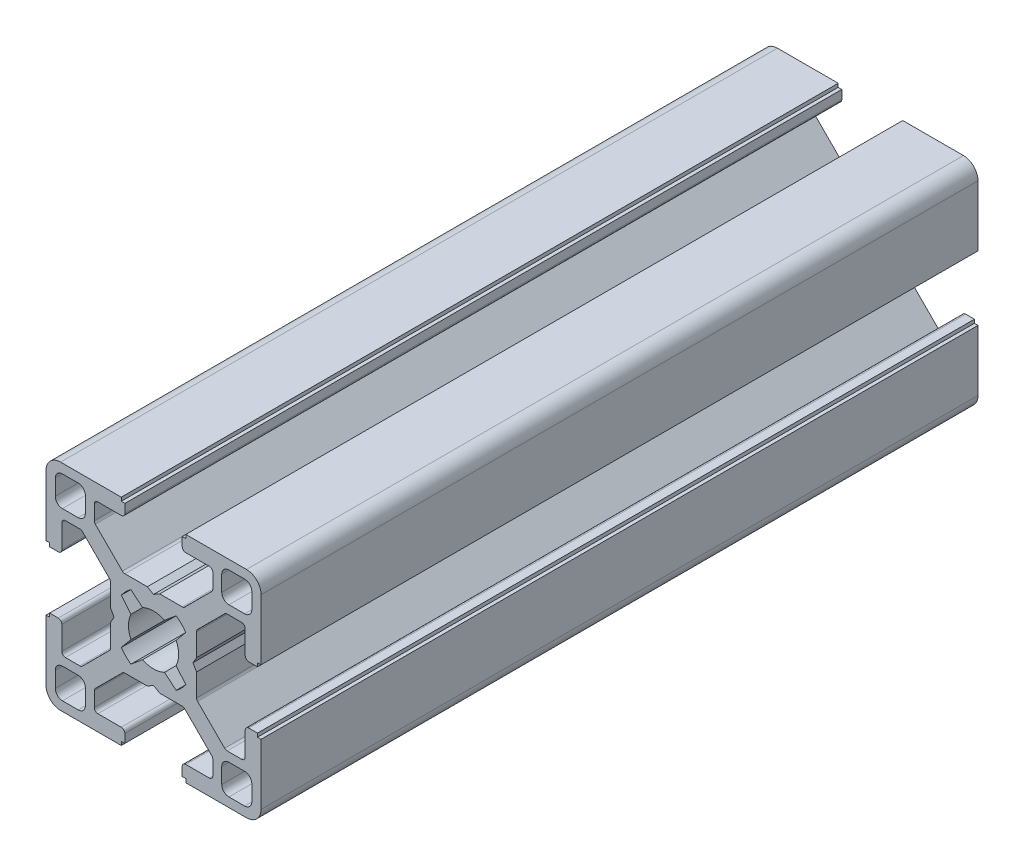
SolidWorks part; units mm, degrees
ref_plane "Front Plane" through (0, 0, 0) normal (0, 0, 1) x (1, 0, 0)
ref_plane "Top Plane" through (0, 0, 0) normal (0, 1, 0) x (1, 0, 0)
ref_plane "Right Plane" through (0, 0, 0) normal (1, 0, 0) x (0, 0, -1)
sketch "Sketch1" plane through (0, 0, 0) normal (0, 0, 1) x (1, 0, 0)
  line L0 (-15, 0) -> (15, 0) construction
  line L1 (0, -15) -> (0, 15) construction
  line L2 (-4.5, 15) -> (4.5, 15) construction
  line L3 (-4, -15) -> (4, -15) construction
  line L4 (-4.5, 15) -> (-4.5, 14.5)
  line L5 (-4.5, 14.5) -> (-4, 14.5)
  line L6 (-4, 14.5) -> (-4, 13.29)
  line L7 (-4.5, 12.79) -> (-7.7675, 12.79)
  line L8 (-8.2675, 12.29) -> (-8.2675, 10.2707)
  line L9 (-8.1211, 9.9171) -> (-4.3504, 6.1464)
  line L10 (-3.9968, 6) -> (0, 6)
  line L11 (0, 0) -> (-15, 15) construction
  line L12 (-4.5, 15) -> (-12.968, 15)
  line L14 (-12.705, 9.5135) -> (-10.5135, 9.5135)
  line L15 (-13.705, 10.5135) -> (-13.705, 12.705)
  line L16 (-12.705, 13.705) -> (-10.5135, 13.705)
  line L17 (-9.5135, 10.5135) -> (-9.5135, 12.705)
  line L18 (-13.705, 9.5135) -> (-9.5135, 13.705) construction
  line L19 (-13.705, 13.705) -> (-9.5135, 9.5135) construction
  line L20 (-3.1568, 4.5038) -> (-1.5303, 3.1477) construction
  line L21 (-4.5038, 3.1568) -> (-3.1477, 1.5303) construction
  line L22 (-6, 3.9968) -> (-6, 0)
  line L23 (-9.9171, 8.1211) -> (-6.1464, 4.3504)
  line L24 (-15, 4.5) -> (-15, 12.968)
  line L25 (-12.29, 8.2675) -> (-10.2707, 8.2675)
  line L26 (-12.79, 4.5) -> (-12.79, 7.7675)
  line L27 (-14.5, 4) -> (-13.29, 4)
  line L28 (-14.5, 4.5) -> (-14.5, 4)
  line L29 (-15, 4.5) -> (-14.5, 4.5)
  circle A0 centre (0, 0) radius 3.5
  arc A1 (-12.968, 15) -> (-15, 12.968) centre (-12.968, 12.968) ccw
  circle A2 centre (0, 0) radius 5.5 construction
  arc A3 (-10.5135, 9.5135) -> (-9.5135, 10.5135) centre (-10.5135, 10.5135) ccw
  arc A4 (-13.705, 12.705) -> (-12.705, 13.705) centre (-12.705, 12.705) cw
  arc A5 (-10.5135, 13.705) -> (-9.5135, 12.705) centre (-10.5135, 12.705) cw
  arc A6 (-12.705, 9.5135) -> (-13.705, 10.5135) centre (-12.705, 10.5135) cw
  arc A7 (-12.79, 4.5) -> (-13.29, 4) centre (-13.29, 4.5) cw
  arc A8 (-12.29, 8.2675) -> (-12.79, 7.7675) centre (-12.29, 7.7675) ccw
  arc A9 (-9.9171, 8.1211) -> (-10.2707, 8.2675) centre (-10.2707, 7.7675) ccw
  arc A10 (-6, 3.9968) -> (-6.1464, 4.3504) centre (-6.5, 3.9968) ccw
  arc A11 (-4.3504, 6.1464) -> (-3.9968, 6) centre (-3.9968, 6.5) ccw
  arc A12 (-4, 13.29) -> (-4.5, 12.79) centre (-4.5, 13.29) cw
  arc A13 (-7.7675, 12.79) -> (-8.2675, 12.29) centre (-7.7675, 12.29) ccw
  arc A14 (-8.2675, 10.2707) -> (-8.1211, 9.9171) centre (-7.7675, 10.2707) ccw
  point P4 (0, 0)
  point P8 (0, 0)
  point P13 (0, 15)
  point P15 (0, -15)
  point P16 (0, 6)
  point P23 (-11.6092, 11.6093)
  point P26 (0, 6)
  point P62 (-12.79, 4)
  point P65 (-12.79, 8.2675)
  point P68 (-10.0636, 8.2675)
  point P71 (-6, 4.2039)
  point P74 (-4.2039, 6)
  point P77 (-4, 12.79)
  point P80 (-8.2675, 12.79)
  point P83 (-8.2675, 10.0636)
  dimension "Center Hole Diameter" = 7
  dimension "D11" = 2.032
  dimension "D9" = 11
  dimension "D13" = 1
  dimension "D14" = 0.5
  dimension "Rail Height" = 30
  dimension "Rail Width" = 30
  dimension "T-Slot Width" = 8
  dimension "T-Slot Depth" = 9
  dimension "D1" = 9
  dimension "D2" = 45
  dimension "D3" = 8
  dimension "D4" = 2.21
  dimension "D5" = 16.535
  dimension "D7" = 2.54
  dimension "D6" = 1.295
  dimension "D8" = 1.246
  dimension "D10" = 10.36
  dimension "D12" = 1.905
sketch "Sketch2" plane through (0, 0, 0) normal (1, 0, 0) x (0, 0, -1)
  line L0 (-76.2, 0) -> (76.2, 0) construction
  line L2 (0, -15) -> (0, 15) construction
  line L3 (0, -15) -> (0, 15) construction
  line L4 (-76.2, -15) -> (-76.2, 15) construction
  line L5 (76.2, -15) -> (76.2, 15) construction
  point P0 (-38.7, 0)
  point P3 (0, 0)
  point P4 (38.7, 0)
  point P12 (-76.2, 0)
  point P14 (76.2, 0)
  dimension "Length" = 152.4
  dimension "D1" = 37.5
sketch "Sketch3" plane through (0, 0, 0) normal (0, 0, 1) x (1, 0, 0)
  line L0 (-4.5038, 3.1568) -> (-3.1477, 1.5303)
  line L1 (0, 3.5) -> (0, 5.5)
  line L2 (-5.5, 0) -> (-3.5, 0)
  line L7 (-6, 3.9968) -> (-6, 0) construction
  line L31 (-9.9171, 8.1211) -> (-6.1464, 4.3504) construction
  line L117 (-12.29, 8.2675) -> (-10.2707, 8.2675) construction
  line L118 (-12.79, 4.5) -> (-12.79, 7.7675) construction
  line L157 (-12.705, 9.5135) -> (-10.5135, 9.5135)
  line L158 (-9.5135, 10.5135) -> (-9.5135, 12.705)
  line L163 (-10.5135, 13.705) -> (-12.705, 13.705)
  line L164 (-13.705, 12.705) -> (-13.705, 10.5135)
  line L165 (-12.705, 9.5135) -> (-10.5135, 9.5135)
  line L166 (-9.5135, 10.5135) -> (-9.5135, 12.705)
  line L167 (-10.5135, 13.705) -> (-12.705, 13.705)
  line L168 (-13.705, 12.705) -> (-13.705, 10.5135)
  line L169 (-14.5, 4) -> (-13.29, 4) construction
  line L170 (-14.5, 4.5) -> (-14.5, 4) construction
  line L171 (-15, 4.5) -> (-14.5, 4.5) construction
  line L172 (-15, 4.5) -> (-15, 12.968) construction
  line L173 (-4.5, 15) -> (-12.968, 15) construction
  line L174 (-4.5, 15) -> (-4.5, 14.5) construction
  line L175 (-4.5, 14.5) -> (-4, 14.5) construction
  line L176 (-4, 14.5) -> (-4, 13.29) construction
  line L177 (-4.5, 12.79) -> (-7.7675, 12.79) construction
  line L178 (-8.2675, 12.29) -> (-8.2675, 10.2707) construction
  line L179 (-8.1211, 9.9171) -> (-4.3504, 6.1464) construction
  line L180 (-3.9968, 6) -> (0, 6) construction
  line L181 (-6, 3.9968) -> (-6, 0.866)
  line L182 (-9.9171, 8.1211) -> (-6.1464, 4.3504)
  line L183 (-12.29, 8.2675) -> (-10.2707, 8.2675)
  line L184 (-12.79, 4.5) -> (-12.79, 7.7675)
  line L185 (-14.5, 4) -> (-13.29, 4)
  line L186 (-14.5, 4.5) -> (-14.5, 4)
  line L187 (-15, 4.5) -> (-14.5, 4.5)
  line L188 (-15, 4.5) -> (-15, 12.968)
  line L189 (-4.5, 15) -> (-12.968, 15)
  line L190 (-4.5, 15) -> (-4.5, 14.5)
  line L191 (-4.5, 14.5) -> (-4, 14.5)
  line L192 (-4, 14.5) -> (-4, 13.29)
  line L193 (-4.5, 12.79) -> (-7.7675, 12.79)
  line L194 (-8.2675, 12.29) -> (-8.2675, 10.2707)
  line L195 (-8.1211, 9.9171) -> (-4.3504, 6.1464)
  line L196 (-3.9968, 6) -> (-0.866, 6)
  line L197 (-0.866, 6) -> (0, 5.5)
  line L198 (0, -15) -> (0, 15) construction
  line L199 (0, 0) -> (-15, 15) construction
  line L200 (0, 0) -> (-15, 15) construction
  line L201 (-3.1568, 4.5038) -> (-1.5303, 3.1477) construction
  line L202 (-3.1568, 4.5038) -> (-1.5303, 3.1477)
  line L203 (-6, 0.866) -> (-5.5, 0)
  line L204 (-15, 0) -> (15, 0) construction
  line L205 (-15, 0) -> (15, 0) construction
  line L206 (0, -15) -> (0, 15) construction
  arc A0 (-3.5, 0) -> (-3.1477, 1.5303) centre (0, 0) cw
  arc A10 (-6, 3.9968) -> (-6.1464, 4.3504) centre (-6.5, 3.9968) ccw construction
  circle A16 centre (0, 0) radius 3.5
  arc A18 (0, 3.5) -> (-1.5303, 3.1477) centre (0, 0) ccw
  arc A20 (-9.9171, 8.1211) -> (-10.2707, 8.2675) centre (-10.2707, 7.7675) ccw construction
  arc A22 (-12.29, 8.2675) -> (-12.79, 7.7675) centre (-12.29, 7.7675) ccw construction
  arc A28 (-13.29, 4) -> (-12.79, 4.5) centre (-13.29, 4.5) ccw construction
  arc A29 (-10.5135, 9.5135) -> (-9.5135, 10.5135) centre (-10.5135, 10.5135) ccw
  arc A30 (-9.5135, 12.705) -> (-10.5135, 13.705) centre (-10.5135, 12.705) ccw
  arc A31 (-12.705, 13.705) -> (-13.705, 12.705) centre (-12.705, 12.705) ccw
  arc A32 (-13.705, 10.5135) -> (-12.705, 9.5135) centre (-12.705, 10.5135) ccw
  arc A33 (-10.5135, 9.5135) -> (-9.5135, 10.5135) centre (-10.5135, 10.5135) ccw
  arc A34 (-9.5135, 12.705) -> (-10.5135, 13.705) centre (-10.5135, 12.705) ccw
  arc A35 (-12.705, 13.705) -> (-13.705, 12.705) centre (-12.705, 12.705) ccw
  arc A36 (-13.705, 10.5135) -> (-12.705, 9.5135) centre (-12.705, 10.5135) ccw
  arc A37 (-12.968, 15) -> (-15, 12.968) centre (-12.968, 12.968) ccw construction
  arc A38 (-4.5, 12.79) -> (-4, 13.29) centre (-4.5, 13.29) ccw construction
  arc A39 (-7.7675, 12.79) -> (-8.2675, 12.29) centre (-7.7675, 12.29) ccw construction
  arc A40 (-8.2675, 10.2707) -> (-8.1211, 9.9171) centre (-7.7675, 10.2707) ccw construction
  arc A41 (-4.3504, 6.1464) -> (-3.9968, 6) centre (-3.9968, 6.5) ccw construction
  arc A42 (-6, 3.9968) -> (-6.1464, 4.3504) centre (-6.5, 3.9968) ccw
  arc A43 (-9.9171, 8.1211) -> (-10.2707, 8.2675) centre (-10.2707, 7.7675) ccw
  arc A44 (-12.29, 8.2675) -> (-12.79, 7.7675) centre (-12.29, 7.7675) ccw
  arc A45 (-13.29, 4) -> (-12.79, 4.5) centre (-13.29, 4.5) ccw
  arc A46 (-12.968, 15) -> (-15, 12.968) centre (-12.968, 12.968) ccw
  arc A47 (-4.5, 12.79) -> (-4, 13.29) centre (-4.5, 13.29) ccw
  arc A48 (-7.7675, 12.79) -> (-8.2675, 12.29) centre (-7.7675, 12.29) ccw
  arc A49 (-8.2675, 10.2707) -> (-8.1211, 9.9171) centre (-7.7675, 10.2707) ccw
  arc A50 (-4.3504, 6.1464) -> (-3.9968, 6) centre (-3.9968, 6.5) ccw
  circle A51 centre (0, 0) radius 5.5 construction
  arc A52 (-3.1568, 4.5038) -> (-4.5038, 3.1568) centre (0, 0) ccw
  dimension "D3" = 60
  dimension "D4" = 60
  dimension "D1" = 0
  dimension "D2" = 0
extrude "Boss-Extrude1" add sketch "Sketch3" along normal mid plane 100
pattern_circular "CirPattern1" count 4 over 360 about axis through (0, 0, 0) along (0, 0, 1) of "Boss-Extrude1"
ref_plane "Contact Plane1" through (15, 0, 0) normal (1, 0, 0) x (0, 0, -1)
ref_plane "Contact Plane2" through (0, -15, 0) normal (0, 1, 0) x (1, 0, 0)
ref_plane "Contact Plane3" through (-15, 0, 0) normal (1, 0, 0) x (0, 0, -1)
ref_plane "Contact Plane4" through (0, 15, 0) normal (0, 1, 0) x (1, 0, 0)
equation "\"D1@Sketch2\" = \"Rail Height@Sketch1\" * 1.25"
equation "\"D1@Sketch1\"=\"T-Slot Width@Sketch1\"+1mm"
equation "\"D3@Sketch1\"=\"T-Slot Width@Sketch1\""
equation "\"D1@Boss-Extrude1\"=\"length\""
equation "\"length\"= 100"
